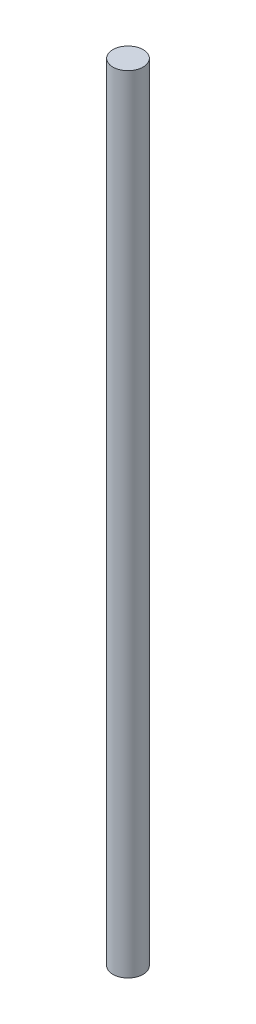
SolidWorks part; units mm, degrees
ref_plane "前视基准面" through (0, 0, 0) normal (0, 0, 1) x (1, 0, 0)
ref_plane "上视基准面" through (0, 0, 0) normal (0, 1, 0) x (1, 0, 0)
ref_plane "右视基准面" through (0, 0, 0) normal (1, 0, 0) x (0, 0, -1)
sketch "草图1" plane through (0, 0, 0) normal (0, 1, 0) x (1, 0, 0)
  circle A0 centre (0, 0) radius 2.5
  dimension "D1" = 5
extrude "凸台-拉伸1" add sketch "草图1" along normal blind 130 contours A0
